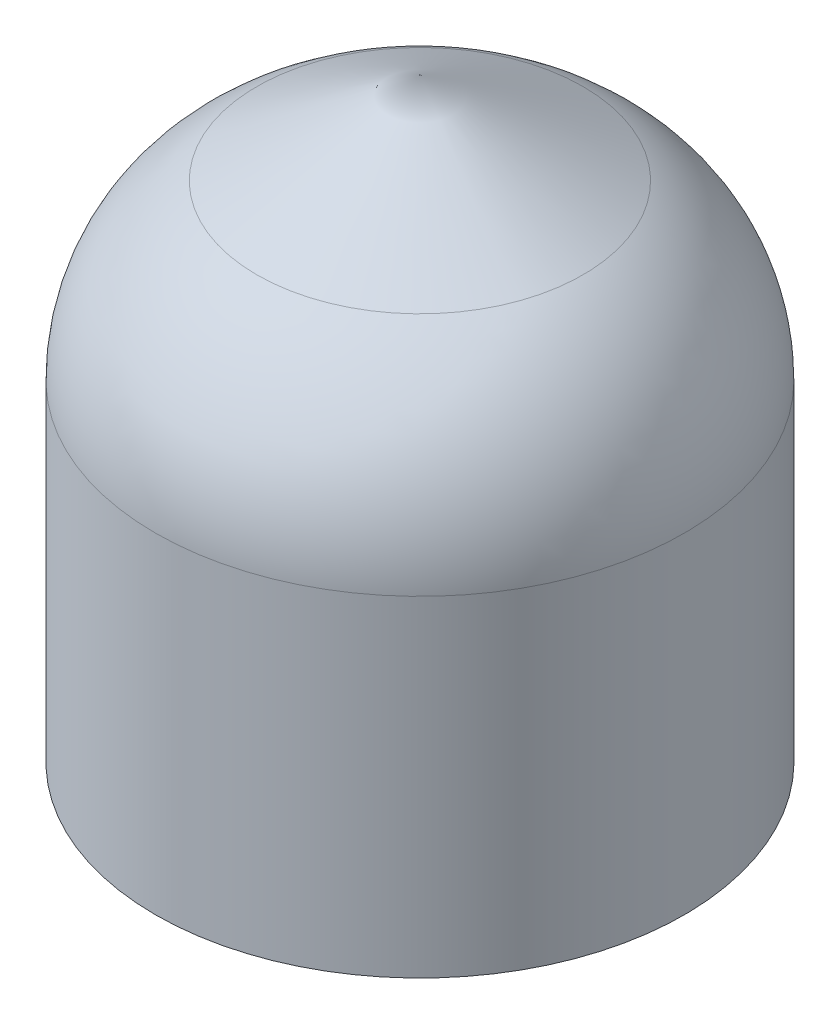
SolidWorks part; units mm, degrees
ref_plane "Alzado" through (0, 0, 0) normal (0, 0, 1) x (1, 0, 0)
ref_plane "Planta" through (0, 0, 0) normal (0, 1, 0) x (1, 0, 0)
ref_plane "Vista lateral" through (0, 0, 0) normal (1, 0, 0) x (0, 0, -1)
sketch "Croquis2" plane through (0, 0, 0) normal (0, 0, 1) x (1, 0, 0)
  line L0 (0, 5.6618) -> (0, 0) construction
  line L1 (-2.5, 0) -> (-4, 0)
  line L2 (-4, 0) -> (-4, 5)
  line L3 (-2.4671, 7.6168) -> (0, 9)
  line L4 (0, 9) -> (0, 7)
  line L5 (0, 7) -> (-2.5, 7)
  line L6 (-2.5, 7) -> (-2.5, 0)
  line L7 (0, 0) -> (-4.686, 0) construction
  arc A0 (-4, 5) -> (-2.4671, 7.6168) centre (-1, 5) cw
  point P7 (-4, 2.1946)
  point P13 (-4, 0.416)
  point P14 (-1.6655, 3.6211)
  point P15 (0, 0)
  dimension "D5" = 3
  dimension "D1" = 5
  dimension "D2" = 8
  dimension "D3" = 7
  dimension "D4" = 9
  dimension "D6" = 5
revolve "Revolución1" add sketch "Croquis2" angle 360 about L0
